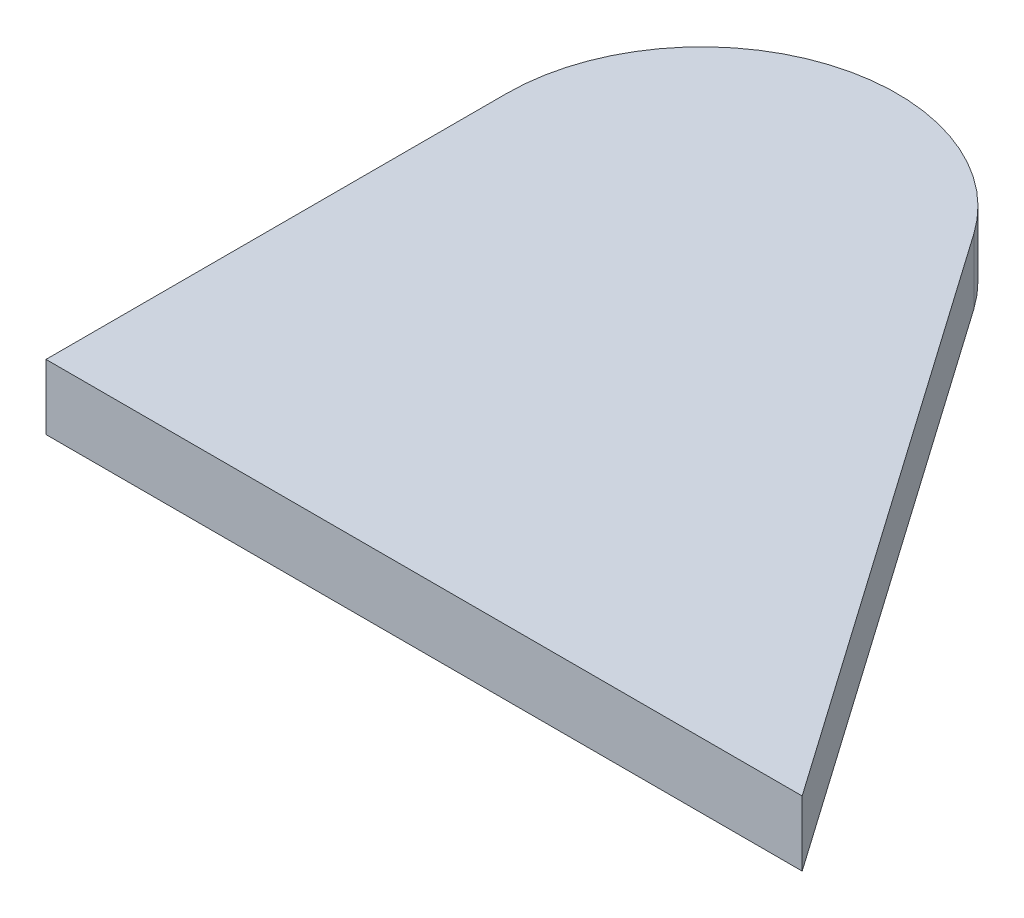
SolidWorks part; units mm, degrees
ref_plane "Front Plane" through (0, 0, 0) normal (0, 0, 1) x (1, 0, 0)
ref_plane "Top Plane" through (0, 0, 0) normal (0, 1, 0) x (1, 0, 0)
ref_plane "Right Plane" through (0, 0, 0) normal (1, 0, 0) x (0, 0, -1)
sketch "Sketch1" plane through (0, 0, 0) normal (0, 1, 0) x (1, 0, 0)
  line L0 (19.05, 63.5) -> (19.05, 0) construction
  line L5 (19.05, 0) -> (73.7608, 0)
  line L6 (73.7608, 0) -> (34.6548, 55.8491)
  line L7 (0, 0) -> (19.05, 0)
  line L8 (8.89, 28.808) -> (8.89, 8.89)
  line L9 (0, 0) -> (0, 44.9225)
  line L10 (8.89, 8.89) -> (34.29, 8.89)
  line L11 (34.29, 8.89) -> (24.1219, 26.56)
  line L12 (32.8162, 31.7545) -> (46.99, 8.89)
  line L13 (46.99, 8.89) -> (72.39, 8.89)
  line L14 (72.39, 8.89) -> (35.2484, 34.8968)
  arc A1 (34.6548, 55.8491) -> (0, 44.9225) centre (19.05, 44.9225) ccw
  circle A2 centre (19.05, 44.9225) radius 4.7625
  arc A3 (8.89, 28.808) -> (24.1219, 26.56) centre (19.05, 44.9225) ccw
  arc A4 (34.6548, 55.8491) -> (0, 44.9225) centre (19.05, 44.9225) ccw
  arc A5 (32.8162, 31.7545) -> (35.2484, 34.8968) centre (19.05, 44.9225) ccw
  dimension "D3" = 38.1
  dimension "D5" = 9.525
  dimension "D1" = 55
  dimension "D2" = 63.5
  dimension "D4" = 55.8491
  dimension "D6" = 8.89
  dimension "D7" = 8.89
  dimension "D8" = 35
  dimension "D9" = 25.4
  dimension "D10" = 8.89
  dimension "D11" = 12.7
  dimension "D12" = 25.4
extrude "Boss-Extrude2" add sketch "Sketch1" along normal blind 6.35 contours L9 L7 L5 L6 A1
